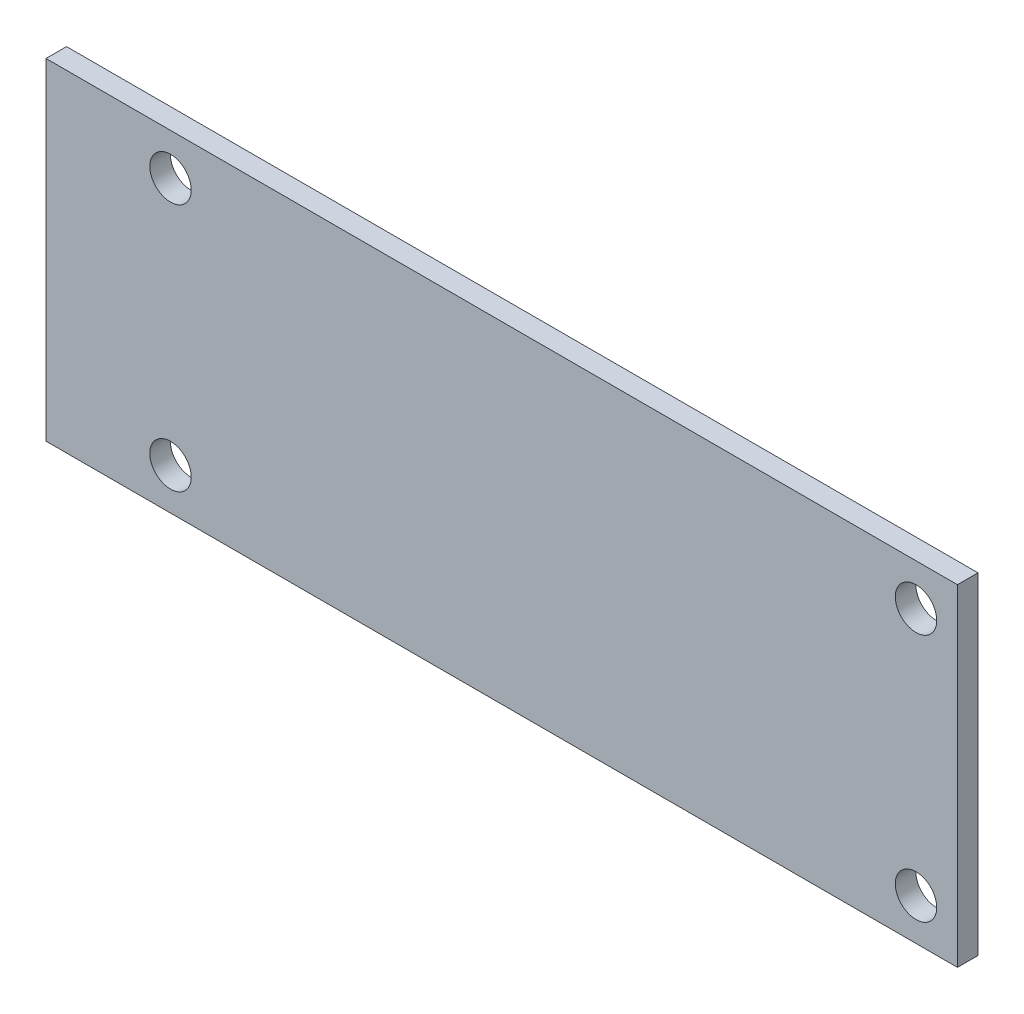
SolidWorks part; units mm, degrees
material "Printed Circuit Board"
ref_plane "Front Plane" through (0, 0, 0) normal (0, 0, 1) x (1, 0, 0)
ref_plane "Top Plane" through (0, 0, 0) normal (0, 1, 0) x (1, 0, 0)
ref_plane "Right Plane" through (0, 0, 0) normal (1, 0, 0) x (0, 0, -1)
sketch "Sketch1" plane through (0, 0, 0) normal (0, 0, 1) x (1, 0, 0)
  line L1 (-34.925, -12.7) -> (34.925, -12.7)
  line L2 (-34.925, -12.7) -> (-34.925, 12.7)
  line L3 (-34.925, 12.7) -> (34.925, 12.7)
  line L4 (34.925, -12.7) -> (34.925, 12.7)
  line L5 (-34.925, -12.7) -> (34.925, 12.7) construction
  line L6 (-34.925, 12.7) -> (34.925, -12.7) construction
  point P0 (0, 0)
  dimension "D1" = 69.85
  dimension "D2" = 25.4
extrude "Extrude1" add sketch "Sketch1" along normal blind 1.5748
sketch "Sketch2" plane through (0, 0, 1.5748) normal (0, 0, 1) x (1, 0, 0)
  line L0 (-34.925, 9.525) -> (-25.3822, 9.525) construction
  line L1 (-34.925, 12.7) -> (-34.925, -12.7) construction
  line L2 (-25.3822, 9.525) -> (31.75, 9.525) construction
  dimension "D1" = 9.5428
  dimension "D2" = 66.675
  dimension "D3" = 3.175
hole_wizard "1/8 (0.125) Diameter Hole1" positions "3DSketch1" profile "Sketch3" hole size "1/8" standard "Ansi Inch"
sketch3d "3DSketch1"
  point P0 (-25.3822, 9.525, 1.5748)
  point P3 (31.75, 9.525, 1.5748)
sketch "Sketch3" plane through (-25.3822, 9.525, 1.5748) normal (1, 0, 0) x (0, -1, 0)
  line L0 (0, 0) -> (0, 16.9559)
  line L1 (0, 16.9559) -> (1.5875, 16.002)
  line L2 (1.5875, 16.002) -> (1.5875, 0)
  line L5 (1.5875, 0) -> (0, 0)
  line L10 (0, 16.9559) -> (-1.5875, 16.002) construction
  line L11 (0, -6.35) -> (0, 107.95) construction
  dimension "Hole Dia." = 3.175
  dimension "Hole Depth" = 16.002
  dimension "Drill Angle" = 118
mirror "Mirror1" about plane through (0, 0, 0) normal (0, 1, 0) of "1/8 (0.125) Diameter Hole1"
